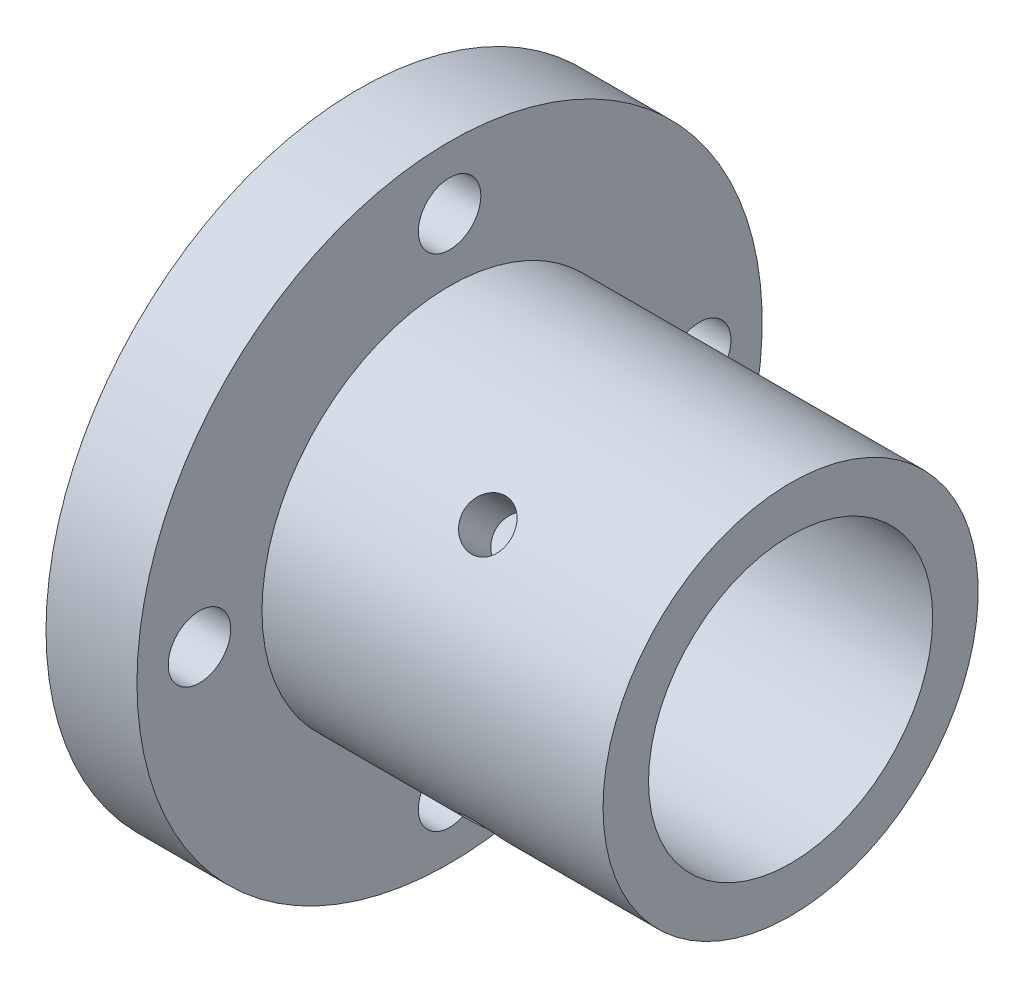
SolidWorks part; units mm, degrees
ref_plane "Front Plane" through (0, 0, 0) normal (0, 0, 1) x (1, 0, 0)
ref_plane "Top Plane" through (0, 0, 0) normal (0, 1, 0) x (1, 0, 0)
ref_plane "Right Plane" through (0, 0, 0) normal (1, 0, 0) x (0, 0, -1)
sketch "Sketch1" plane through (0, 0, 0) normal (0, 0, 1) x (1, 0, 0)
  line L0 (0, 0) -> (38, 0) construction
  line L1 (0, 12.5) -> (0, 27.5)
  line L2 (0, 27.5) -> (8, 27.5)
  line L3 (8, 27.5) -> (8, 16.5)
  line L4 (8, 16.5) -> (38, 16.5)
  line L5 (38, 16.5) -> (38, 12.5)
  line L6 (38, 12.5) -> (0, 12.5)
  dimension "D" = 25
  dimension "H" = 55
  dimension "T" = 8
  dimension "L" = 38
  dimension "D1." = 33
  dimension "N" = 4
revolve "Revolve1" add sketch "Sketch1" angle 360 about L0
ref_plane "Plane1" through (0, 0, 0) normal (0, 0.7071, 0.7071) x (1, 0, 0)
ref_plane "Plane2" through (0, 11.6673, 11.6673) normal (0, 0.7071, 0.7071) x (1, 0, 0)
hole_wizard "Tapped Hole1" positions "Sketch3" profile "Sketch2" tap size "M5x0.8" standard "JIS"
sketch "Sketch3" plane through (84.6883, 3.2175, 20.1171) normal (0, 0.7071, 0.7071) x (1, 0, 0)
  line L1 (-84.6883, 39.4498) -> (-84.6883, -15.5502) construction
  point P0 (-61.6883, 11.9498)
  dimension "L_s" = 23
sketch "Sketch2" plane through (23, 11.6673, 11.6673) normal (1, 0, 0) x (0, -0.7071, 0.7071)
  line L0 (0, 0) -> (0, 33)
  line L1 (0, 33) -> (2.1, 33)
  line L2 (2.1, 33) -> (2.1, 0)
  line L5 (2.1, 0) -> (0, 0)
  line L11 (0, 0) -> (0, 33) construction
  dimension "Thru Tap Drill Dia." = 4.2
  dimension "Thru Tap Drill Depth" = 33
cosmetic thread "Hole Thread6" parameters "M"=5
pattern_circular "CirPattern1" count 2 every 90 about axis through (0, 0, 0) along (-1, 0, 0) of "Tapped Hole1"
hole_wizard "Diameter Hole1" positions "Sketch5" profile "Sketch4" hole size "Ø3.5" standard "JIS" end condition through all
sketch "Sketch5" plane through (8, 0, 0) normal (1, 0, 0) x (0, 0, -1)
  line L0 (0, 22) -> (0, -22) construction
  point P0 (0, 22)
  point P4 (0, -22)
  dimension "P" = 44
sketch "Sketch4" plane through (8, 22, 0) normal (0, 1, 0) x (0, 0, -1)
  line L0 (0, 0) -> (0, 8)
  line L1 (0, 8) -> (2.75, 8)
  line L2 (2.75, 8) -> (2.75, 0)
  line L5 (2.75, 0) -> (0, 0)
  line L11 (0, 0) -> (0, 8) construction
  dimension "Thru Hole Depth" = 8
  dimension "D1_s" = 5.5
hole_wizard "Diameter Hole2" positions "Sketch7" profile "Sketch6" hole size "Ø3.5" standard "JIS" end condition through all
sketch "Sketch7" plane through (8, 0, 0) normal (1, 0, 0) x (0, 0, -1)
  line L0 (-22, 0) -> (22, 0) construction
  point P0 (-22, 0)
  point P2 (22, 0)
  dimension "P" = 44
sketch "Sketch6" plane through (8, 0, 22) normal (0, 1, 0) x (0, 0, -1)
  line L0 (0, 0) -> (0, 8)
  line L1 (0, 8) -> (2.75, 8)
  line L2 (2.75, 8) -> (2.75, 0)
  line L5 (2.75, 0) -> (0, 0)
  line L11 (0, 0) -> (0, 8) construction
  dimension "Thru Hole Depth" = 8
  dimension "D1_s" = 5.5
hole_wizard "Tapped Hole2" [suppressed] positions "Sketch9" profile "Sketch8" tap size "M4x0.7" standard "JIS"
sketch "Sketch9" [suppressed] plane through (0, 0, 0) normal (-1, 0, 0) x (0, 0, 1)
  line L2 (0, 10) -> (0, -10) construction
  point P0 (0, 10)
  point P4 (0, -10)
  dimension "P" = 44
sketch "Sketch8" [suppressed] plane through (0, 10, 0) normal (0, 1, 0) x (0, 0, 1)
  line L0 (0, 0) -> (0, 5)
  line L1 (0, 5) -> (1.65, 5)
  line L2 (1.65, 5) -> (1.65, 0)
  line L5 (1.65, 0) -> (0, 0)
  line L11 (0, 0) -> (0, 5) construction
  dimension "Thru Tap Drill Dia." = 3.3
  dimension "Thru Tap Drill Depth" = 5
cosmetic thread "Hole Thread1" [suppressed] parameters "M1"=4
cosmetic thread "Hole Thread2" [suppressed] parameters "M1"=4
hole_wizard "Tapped Hole3" [suppressed] positions "Sketch11" profile "Sketch10" tap size "M4x0.7" standard "JIS"
sketch "Sketch11" [suppressed] plane through (0, 0, 0) normal (-1, 0, 0) x (0, 0, 1)
  line L0 (-10, 0) -> (10, 0) construction
  point P0 (-10, 0)
  point P2 (10, 0)
  dimension "P" = 44
sketch "Sketch10" [suppressed] plane through (0, 0, -10) normal (0, 1, 0) x (0, 0, 1)
  line L0 (0, 0) -> (0, 5)
  line L1 (0, 5) -> (1.65, 5)
  line L2 (1.65, 5) -> (1.65, 0)
  line L5 (1.65, 0) -> (0, 0)
  line L11 (0, 0) -> (0, 5) construction
  dimension "Thru Tap Drill Dia." = 3.3
  dimension "Thru Tap Drill Depth" = 5
cosmetic thread "Hole Thread3" [suppressed] parameters "M1"=4
cosmetic thread "Hole Thread4" [suppressed] parameters "M1"=4
sketch "Sketch12" [suppressed] plane through (0, 0, 0) normal (-1, 0, 0) x (0, 0, 1)
  line L1 (-15.5563, 0) -> (0, 15.5563)
  line L2 (-15.5563, 0) -> (0, -15.5563)
  line L3 (0, -15.5563) -> (15.5563, 0)
  line L4 (0, 15.5563) -> (15.5563, 0)
  line L5 (-15.5563, 0) -> (15.5563, 0) construction
  line L6 (0, -15.5563) -> (0, 15.5563) construction
  point P0 (0, 0)
  dimension "K" = 22
extrude "Cut-Extrude1" [suppressed] cut sketch "Sketch12" against normal through all flip side to cut
hole_wizard "Diameter Hole3" [suppressed] positions "Sketch14" profile "Sketch13" hole size "Ø3.5" standard "JIS"
sketch "Sketch14" [suppressed] plane through (5, 0, 0) normal (1, 0, 0) x (0, 0, -1)
  circle A0 centre (0, 0) radius 10 construction
  point P0 (0, 10)
  point P4 (0, -10)
  point P28 (-10, 0)
  point P30 (10, 0)
  dimension "P" = 44
sketch "Sketch13" [suppressed] plane through (5, 10, 0) normal (0, 1, 0) x (0, 0, -1)
  line L0 (0, 0) -> (0, 5)
  line L1 (0, 5) -> (1.75, 5)
  line L2 (1.75, 5) -> (1.75, 0)
  line L5 (1.75, 0) -> (0, 0)
  line L11 (0, 0) -> (0, 5) construction
  dimension "Thru Hole Depth" = 5
  dimension "D1_s" = 5.5
equation "\"Plane dim\"= \"D1.@Sketch1\" * 0.5"
